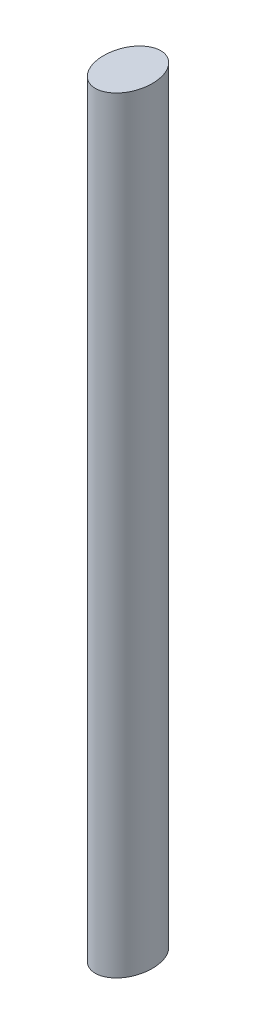
SolidWorks part; units mm, degrees
material "3.0205 (EN-AW 1200)"
ref_plane "Alzado" through (0, 0, 0) normal (0, 0, 1) x (1, 0, 0)
ref_plane "Planta" through (0, 0, 0) normal (0, 1, 0) x (1, 0, 0)
ref_plane "Vista lateral" through (0, 0, 0) normal (1, 0, 0) x (0, 0, -1)
sketch "Croquis2" plane through (0, 0, 0) normal (0, 1, 0) x (1, 0, 0)
  ellipse E0 centre (0, 0) end of major axis (0, 3.2) minor radius 2.375
  dimension "D1" = 6.4
  dimension "D2" = 4.75
extrude "Saliente-Extruir1" add sketch "Croquis2" along normal blind 75
